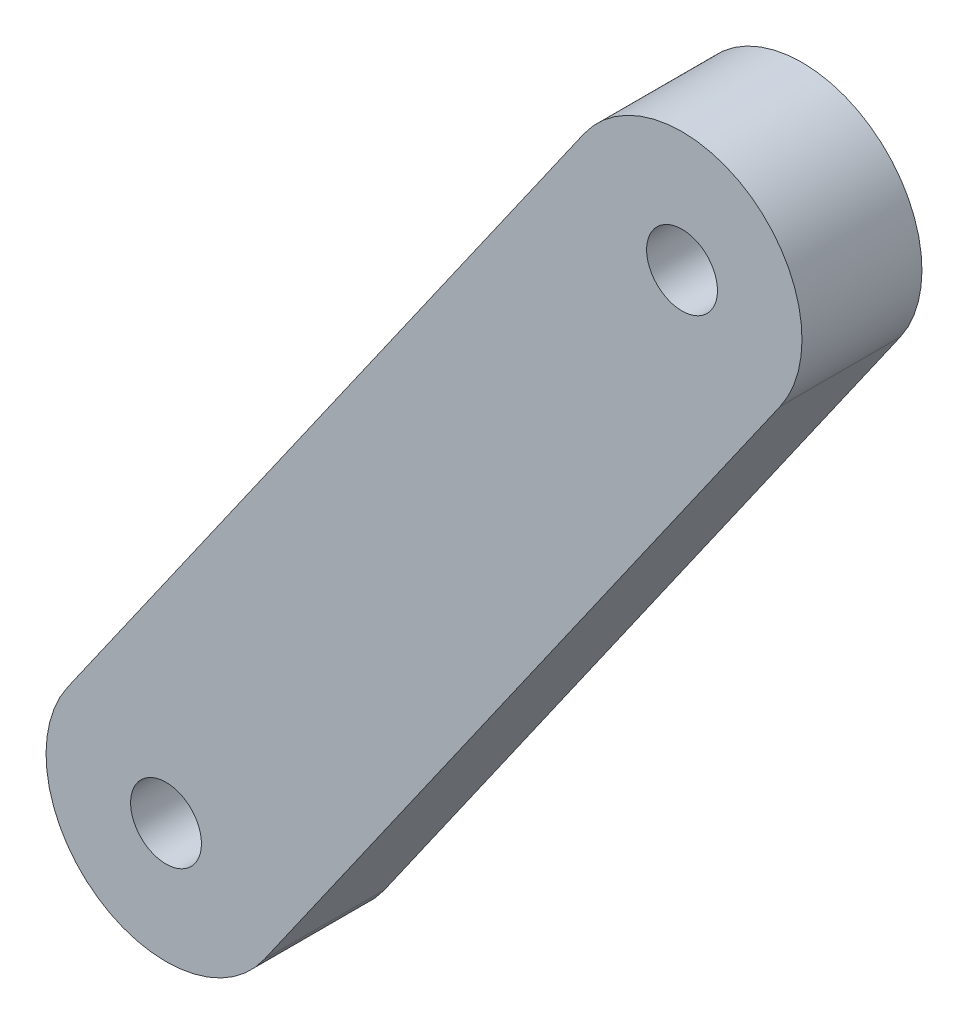
SolidWorks part; units mm, degrees
ref_plane "Front Plane" through (0, 0, 0) normal (0, 0, 1) x (1, 0, 0)
ref_plane "Top Plane" through (0, 0, 0) normal (0, 1, 0) x (1, 0, 0)
ref_plane "Right Plane" through (0, 0, 0) normal (1, 0, 0) x (0, 0, -1)
sketch "Sketch2" plane through (0, 0, 0) normal (0, 0, 1) x (1, 0, 0)
  line L0 (0, 0) -> (21.8533, 31.2097) construction
  line L1 (0, 0) -> (17.0899, 0) construction
  line L2 (21.8533, 31.2097) -> (0, 0) construction
  line L3 (26.0146, 28.2959) -> (4.1613, -2.9138)
  line L4 (17.692, 34.1235) -> (-4.1613, 2.9138)
  arc A0 (26.0146, 28.2959) -> (17.692, 34.1235) centre (21.8533, 31.2097) ccw
  arc A1 (-4.1613, 2.9138) -> (4.1613, -2.9138) centre (0, 0) ccw
  circle A2 centre (21.8533, 31.2097) radius 1.5
  circle A3 centre (0, 0) radius 1.5
  point P3 (10.9266, 15.6048)
  dimension "D4" = 3
  dimension "D1" = 38.1
  dimension "D2" = 55
  dimension "D3" = 10.16
extrude "Boss-Extrude1" add sketch "Sketch2" along normal mid plane 5.08
